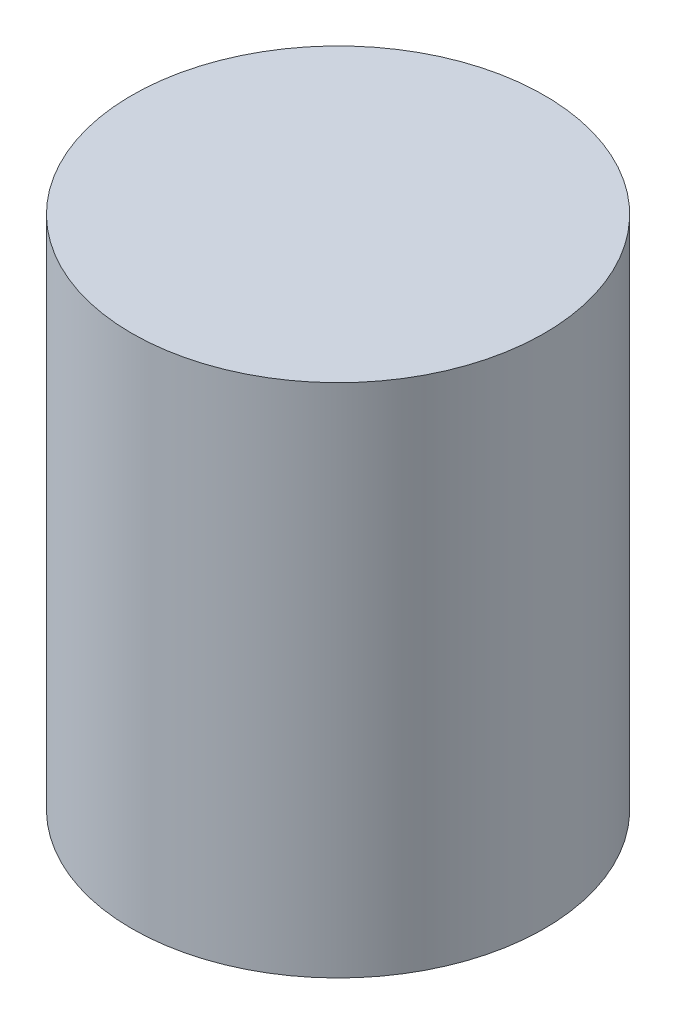
SolidWorks part; units mm, degrees
ref_plane "Front Plane" through (0, 0, 0) normal (0, 0, 1) x (1, 0, 0)
ref_plane "Top Plane" through (0, 0, 0) normal (0, 1, 0) x (1, 0, 0)
ref_plane "Right Plane" through (0, 0, 0) normal (1, 0, 0) x (0, 0, -1)
sketch "Sketch1" plane through (0, 0, 0) normal (0, 0, 1) x (1, 0, 0)
  line L0 (0, 50.6542) -> (0, -49.3458)
  line L1 (0, -49.3458) -> (40, -49.3458)
  line L2 (40, -49.3458) -> (40, 50.6542)
  line L3 (40, 50.6542) -> (0, 50.6542)
  dimension "D1" = 40
  dimension "D2" = 100
revolve "Revolve1" add sketch "Sketch1" angle 360 about L0
